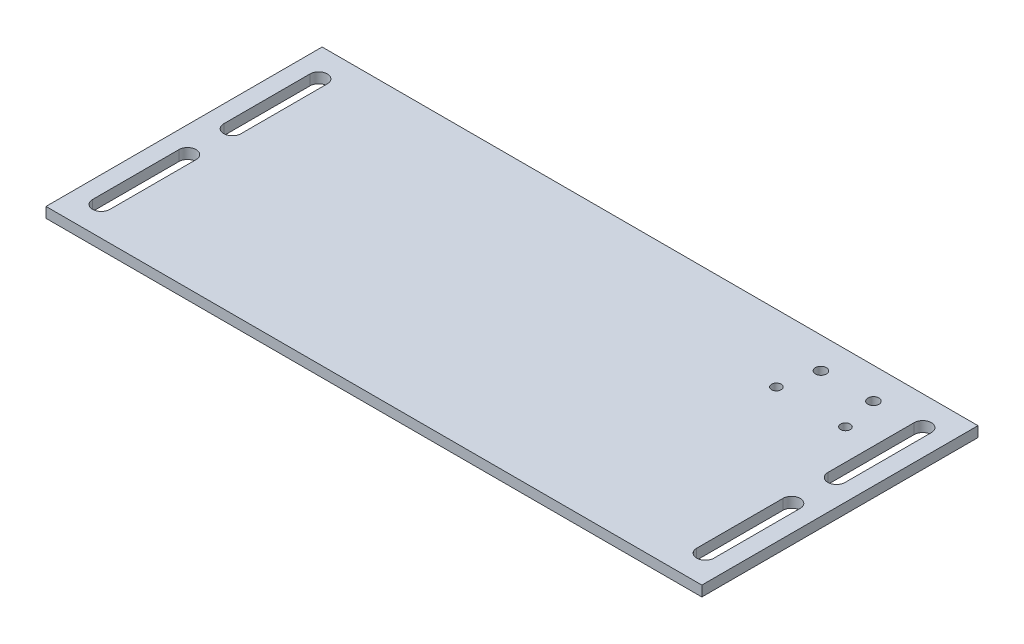
SolidWorks part; units mm, degrees
ref_plane "Front Plane" through (0, 0, 0) normal (0, 0, 1) x (1, 0, 0)
ref_plane "Top Plane" through (0, 0, 0) normal (0, 1, 0) x (1, 0, 0)
ref_plane "Right Plane" through (0, 0, 0) normal (1, 0, 0) x (0, 0, -1)
sketch "Sketch1" plane through (0, 0, 0) normal (0, 1, 0) x (1, 0, 0)
  line L0 (-87.5, 6.5) -> (-87.5, 31.5) construction
  line L1 (-95, 40) -> (95, 40)
  line L2 (-95, 40) -> (-95, -40)
  line L3 (-95, -40) -> (95, -40)
  line L4 (95, 40) -> (95, -40)
  line L5 (-90, 6.5) -> (-90, 31.5)
  line L6 (-85, 6.5) -> (-85, 31.5)
  line L7 (-78.5296, 0) -> (-87.4198, 0) construction
  line L8 (-87.5, -6.5) -> (-87.5, -31.5) construction
  line L9 (-90, -6.5) -> (-90, -31.5)
  line L10 (-85, -6.5) -> (-85, -31.5)
  line L11 (0, -12.4631) -> (0, 23.0704) construction
  line L12 (87.5, 6.5) -> (87.5, 31.5) construction
  line L13 (90, 6.5) -> (90, 31.5)
  line L14 (85, 6.5) -> (85, 31.5)
  line L15 (87.5, -6.5) -> (87.5, -31.5) construction
  line L16 (90, -6.5) -> (90, -31.5)
  line L17 (85, -6.5) -> (85, -31.5)
  arc A0 (-90, 6.5) -> (-85, 6.5) centre (-87.5, 6.5) ccw
  arc A1 (-85, 31.5) -> (-90, 31.5) centre (-87.5, 31.5) ccw
  arc A2 (-90, -6.5) -> (-85, -6.5) centre (-87.5, -6.5) cw
  arc A3 (-85, -31.5) -> (-90, -31.5) centre (-87.5, -31.5) cw
  arc A4 (90, 6.5) -> (85, 6.5) centre (87.5, 6.5) cw
  arc A5 (85, 31.5) -> (90, 31.5) centre (87.5, 31.5) cw
  arc A6 (90, -6.5) -> (85, -6.5) centre (87.5, -6.5) ccw
  arc A7 (85, -31.5) -> (90, -31.5) centre (87.5, -31.5) ccw
  point P4 (0, 40)
  point P5 (95, 0)
  point P9 (-87.5, 19)
  point P18 (-87.5, -19)
  point P23 (-82.9747, 0)
  point P24 (-87.5, 4)
  point P29 (87.5, 19)
  point P36 (87.5, -19)
  dimension "D3" = 30
  dimension "D1" = 190
  dimension "D2" = 80
  dimension "D4" = 5
  dimension "D5" = 5
  dimension "D6" = 4
extrude "Boss-Extrude1" add sketch "Sketch1" along normal blind 3
fillet "Fillet1" [suppressed] radius 5
sketch "Sketch3" plane through (0, 3, 0) normal (0, 1, 0) x (1, 0, 0)
  line L0 (-95, -40) -> (95, -40) construction
  line L1 (-85, -31.5) -> (-85, -6.5) construction
  line L2 (0, -13.3075) -> (0, -37.946) construction
  circle A0 centre (-76, -27.5) radius 1.55
  circle A1 centre (-76, -16) radius 1.55
  circle A2 centre (76, -16) radius 1.55
  circle A3 centre (76, -27.5) radius 1.55
  dimension "D1" = 3.1
  dimension "D2" = 11.5
  dimension "D3" = 12.5
  dimension "D4" = 9
extrude "Cut-Extrude1" [suppressed] cut sketch "Sketch3" against normal up to next
sketch "Sketch4" plane through (0, 3, 0) normal (0, 1, 0) x (1, 0, 0)
  line L0 (95, 40) -> (-95, 40) construction
  line L1 (95, -40) -> (95, 40) construction
  line L2 (56.1, 20.5) -> (76.1, 20.5) construction
  line L3 (58.495, 31) -> (73.705, 31) construction
  circle A0 centre (56.1, 20.5) radius 1.4
  circle A1 centre (76.1, 20.5) radius 1.4
  circle A2 centre (58.495, 31) radius 1.6
  circle A3 centre (73.705, 31) radius 1.6
  point P8 (66.1, 31)
  point P13 (66.1, 20.5)
  dimension "D1" = 9
  dimension "D4" = 3.2
  dimension "D8" = 2.8
  dimension "D2" = 15.21
  dimension "D5" = 19.5
  dimension "D6" = 20
  dimension "D7" = 18.9
extrude "Cut-Extrude2" cut sketch "Sketch4" against normal blind 3
sketch "Sketch5" plane through (0, 3, 0) normal (0, 1, 0) x (1, 0, 0)
  circle A0 centre (76.1, 20.5) radius 3
  circle A1 centre (56.1, 20.5) radius 3
  dimension "D1" = 6
extrude "Cut-Extrude3" [suppressed] cut sketch "Sketch5" against normal blind 2
sketch "Sketch6" [suppressed] plane through (0, 0, 0) normal (0, -1, 0) x (1, 0, 0)
  line L0 (0, 35.1401) -> (0, 10.5699) construction
  line L1 (78.7, 29.0588) -> (76, 30.6177)
  line L2 (76, 30.6177) -> (73.3, 29.0588)
  line L3 (73.3, 29.0588) -> (73.3, 25.9412)
  line L4 (73.3, 25.9412) -> (76, 24.3823)
  line L5 (76, 24.3823) -> (78.7, 25.9412)
  line L6 (78.7, 25.9412) -> (78.7, 29.0588)
  line L7 (78.7, 17.5588) -> (76, 19.1177)
  line L8 (76, 19.1177) -> (73.3, 17.5588)
  line L9 (73.3, 17.5588) -> (73.3, 14.4412)
  line L10 (73.3, 14.4412) -> (76, 12.8823)
  line L11 (76, 12.8823) -> (78.7, 14.4412)
  line L12 (78.7, 14.4412) -> (78.7, 17.5588)
  line L13 (-78.7, 14.4412) -> (-78.7, 17.5588)
  line L14 (-76, 12.8823) -> (-78.7, 14.4412)
  line L15 (-73.3, 14.4412) -> (-76, 12.8823)
  line L16 (-73.3, 17.5588) -> (-73.3, 14.4412)
  line L17 (-76, 19.1177) -> (-73.3, 17.5588)
  line L18 (-78.7, 17.5588) -> (-76, 19.1177)
  line L19 (-78.7, 25.9412) -> (-78.7, 29.0588)
  line L20 (-76, 24.3823) -> (-78.7, 25.9412)
  line L21 (-73.3, 25.9412) -> (-76, 24.3823)
  line L22 (-73.3, 29.0588) -> (-73.3, 25.9412)
  line L23 (-76, 30.6177) -> (-73.3, 29.0588)
  line L24 (-78.7, 29.0588) -> (-76, 30.6177)
  circle A0 centre (76, 27.5) radius 2.7 construction
  circle A1 centre (76, 16) radius 2.7 construction
  circle A2 centre (-76, 16) radius 2.7 construction
  circle A3 centre (-76, 27.5) radius 2.7 construction
  point P10 (76, 16)
  dimension "D1" = 5.4
  dimension "D2" = 5.4
extrude "Cut-Extrude4" [suppressed] cut sketch "Sketch6" against normal blind 2.1
